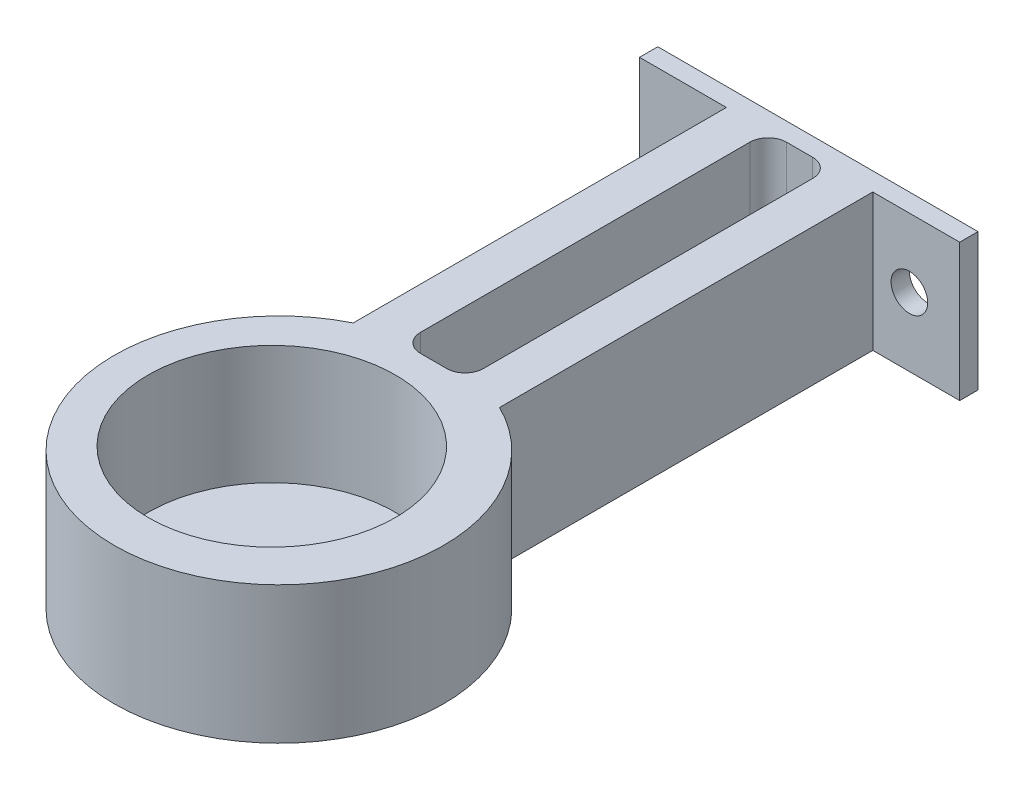
SolidWorks part; units mm, degrees
ref_plane "Front Plane" through (0, 0, 0) normal (0, 0, 1) x (1, 0, 0)
ref_plane "Top Plane" through (0, 0, 0) normal (0, 1, 0) x (1, 0, 0)
ref_plane "Right Plane" through (0, 0, 0) normal (1, 0, 0) x (0, 0, -1)
sketch "草图1" plane through (0, 0, 0) normal (0, 1, 0) x (1, 0, 0)
  line L0 (6.1488, 16.9172) -> (-6.1488, 16.9172)
  arc A0 (-6.1488, 16.9172) -> (6.1488, 16.9172) centre (0, 0) ccw
extrude "凸台-拉伸1" add sketch "草图1" along normal blind 15 contours A0 L0
sketch "草图2" plane through (0, 15, 0) normal (0, 1, 0) x (1, 0, 0)
  circle A0 centre (-0.7757, 0) radius 13.51
sketch "草图3" plane through (0, 0, -16.9172) normal (0, 0, -1) x (-1, 0, 0)
  line L0 (-6.1488, 0) -> (6.1488, 0) construction
  line L1 (-8, 0) -> (8, 0)
  line L2 (0, 0) -> (0, 15)
  line L3 (-8, 15) -> (8, 15)
  line L4 (8, 0) -> (8, 15)
  line L5 (-8, 0) -> (-8, 15)
extrude "凸台-拉伸2" add sketch "草图3" against normal blind 4 contours L4 L3 L5 L1
extrude "切除-拉伸2" cut sketch "草图2" against normal blind 13 contours A0
sketch "草图4" plane through (0, 0, -16.9172) normal (0, 0, -1) x (-1, 0, 0)
  line L0 (-8, 0) -> (8, 0) construction
  line L1 (8, 0) -> (3.4348, 0)
  line L2 (8, 0) -> (8, 15)
  line L3 (8, 15) -> (3.4348, 15)
  line L4 (3.4348, 0) -> (3.4348, 15)
  line L5 (-8, 15) -> (8, 15) construction
  line L6 (0, 0) -> (0, 15)
  line L7 (-8, 15) -> (-3.4348, 15)
  line L8 (-3.4348, 0) -> (-3.4348, 15)
  line L9 (-8, 0) -> (-3.4348, 0)
  line L10 (-8, 0) -> (-8, 15)
  line L11 (8, 0) -> (8, 15) construction
  line M6 (-8, 0) -> (8, 0)
  line M8 (8, 15) -> (-8, 15)
extrude "凸台-拉伸3" add sketch "草图4" along normal blind 40 contours L4 L2 M6 M8 | L10 L8 M6 M8
fillet "圆角2" radius 2 2 edges at (3.4348, 7.5, -16.9172) (-3.4348, 7.5, -16.9172)
sketch "草图5" plane through (0, 0, -56.9172) normal (0, 0, -1) x (-1, 0, 0)
  line L0 (-17.5, 0) -> (-17.5, 15)
  line L1 (8, 0) -> (-17.5, 0)
  line L5 (-17.5, 15) -> (12.5, 15)
  line L6 (0, 0) -> (0, 15)
  line L7 (17.5, 0) -> (17.5, 15)
  line L8 (17.5, 0) -> (8, 0)
  line L9 (17.5, 15) -> (12.5, 15)
  circle A4 centre (-12, 7.5) radius 2
  circle A5 centre (12, 7.5) radius 2
  line M5 (3.4348, 15) -> (3.4348, 0)
  line M6 (3.4348, 0) -> (8, 0)
  line M7 (8, 0) -> (8, 15)
  line M8 (8, 15) -> (3.4348, 15)
extrude "凸台-拉伸4" add sketch "草图5" along normal blind 2 contours L1 L6 L5 L0 A4 | L7 L9 L5 L8 M7 | L6 L1 L5 M5 | M8 M5 M6 M7
fillet "圆角3" radius 2 2 edges at (-3.4348, 7.5, -56.9172) (3.4348, 7.5, -56.9172)
